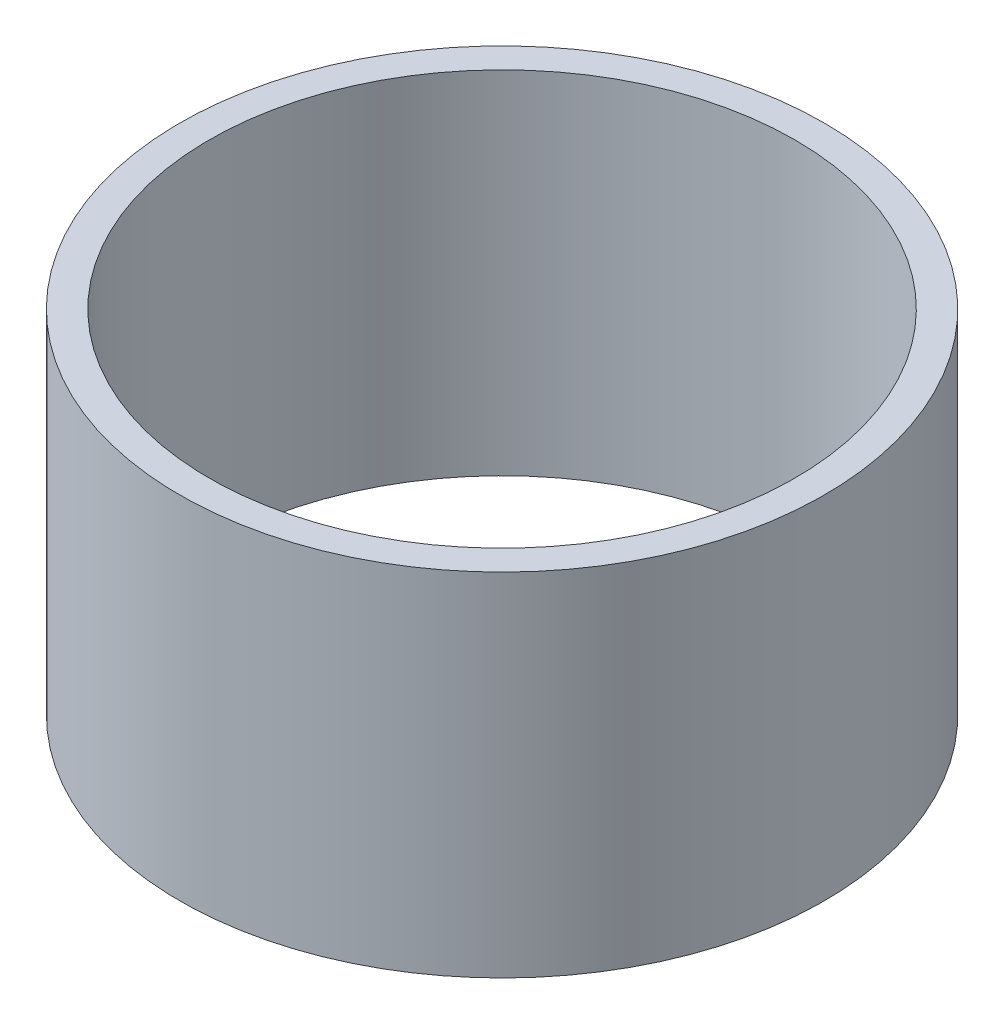
SolidWorks part; units mm, degrees
ref_plane "Front Plane" through (0, 0, 0) normal (0, 0, 1) x (1, 0, 0)
ref_plane "Top Plane" through (0, 0, 0) normal (0, 1, 0) x (1, 0, 0)
ref_plane "Right Plane" through (0, 0, 0) normal (1, 0, 0) x (0, 0, -1)
sketch "Sketch1" plane through (0, 0, 0) normal (0, 1, 0) x (1, 0, 0)
  circle A0 centre (0, 0) radius 31.75
  circle A1 centre (0, 0) radius 34.925
  dimension "D1" = 63.5
  dimension "D2" = 69.85
extrude "Boss-Extrude1" add sketch "Sketch1" along normal blind 38.1
